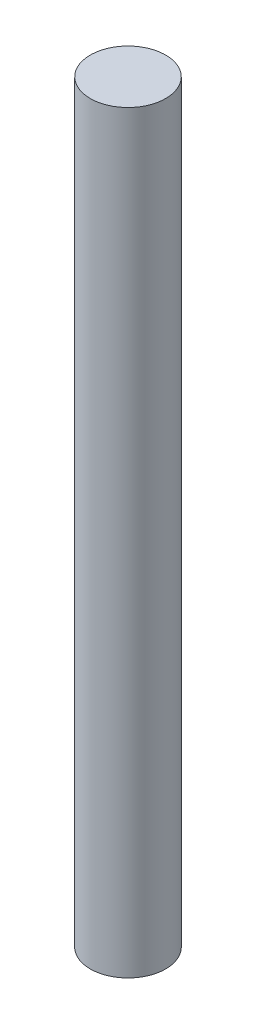
SolidWorks part; units mm, degrees
ref_plane "Front Plane" through (0, 0, 0) normal (0, 0, 1) x (1, 0, 0)
ref_plane "Top Plane" through (0, 0, 0) normal (0, 1, 0) x (1, 0, 0)
ref_plane "Right Plane" through (0, 0, 0) normal (1, 0, 0) x (0, 0, -1)
sketch "Sketch1" plane through (0, 0, 0) normal (0, 1, 0) x (1, 0, 0)
  circle A0 centre (-6.3554, -10.0177) radius 5
  dimension "D1" = 10
extrude "Boss-Extrude1" add sketch "Sketch1" along normal blind 100
